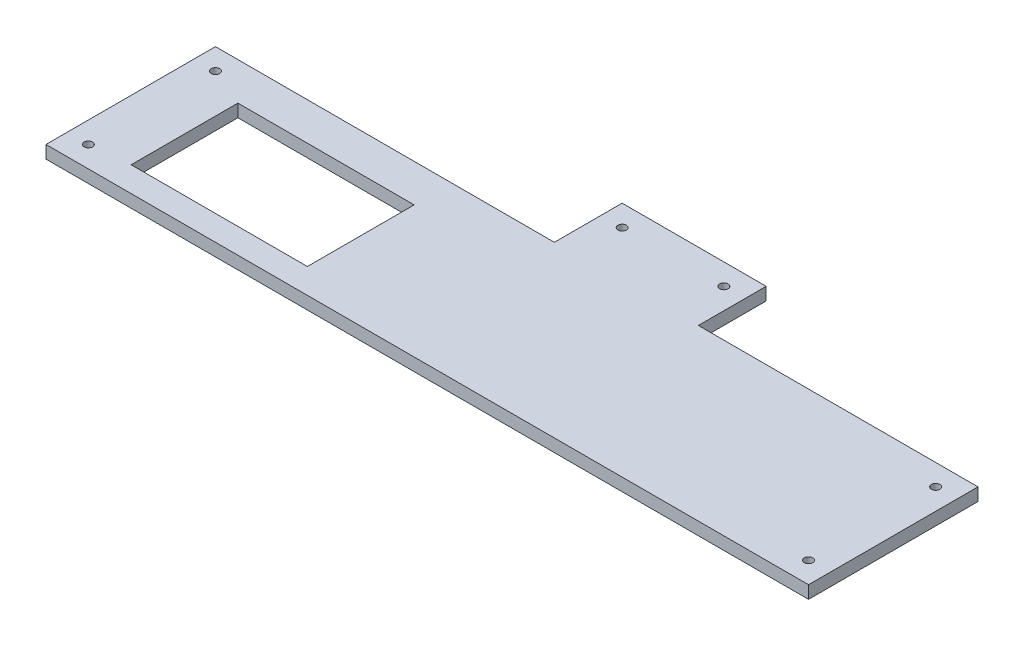
SolidWorks part; units mm, degrees
ref_plane "Front Plane" through (0, 0, 0) normal (0, 0, 1) x (1, 0, 0)
ref_plane "Top Plane" through (0, 0, 0) normal (0, 1, 0) x (1, 0, 0)
ref_plane "Right Plane" through (0, 0, 0) normal (1, 0, 0) x (0, 0, -1)
sketch "Sketch1" plane through (0, 0, 0) normal (0, 1, 0) x (1, 0, 0)
  line L0 (0, 0) -> (-450, 0) construction
  line L1 (0, 0) -> (0, 100) construction
  line L8 (450, 100) -> (-450, 100)
  line L9 (-450, 100) -> (-450, -100)
  line L10 (-450, -100) -> (450, -100)
  line L11 (450, -100) -> (450, 100)
  circle A4 centre (425, -75) radius 5
  circle A5 centre (425, 75) radius 5
  circle A6 centre (-425, -75) radius 5
  circle A7 centre (-425, 75) radius 5
  dimension "D4" = 25
  dimension "D1" = 900
  dimension "D2" = 200
  dimension "D3" = 25
extrude "Boss-Extrude1" add sketch "Sketch1" against normal blind 15
sketch "Sketch2" plane through (0, -15, 0) normal (0, -1, 0) x (1, 0, 0)
  line L1 (-379, 70.5) -> (-171, 70.5)
  line L2 (-379, 70.5) -> (-379, -55.5)
  line L3 (-379, -55.5) -> (-171, -55.5)
  line L4 (-171, 70.5) -> (-171, -55.5)
extrude "Shredder Opening" cut sketch "Sketch2" against normal through all
sketch "Sketch3" plane through (0, 0, 0) normal (0, 1, 0) x (1, 0, 0)
  line L0 (450, 100) -> (-450, 100) construction
  line L1 (120, 100) -> (-50, 100)
  line L2 (120, 100) -> (120, 180)
  line L3 (120, 180) -> (-50, 180)
  line L4 (-50, 100) -> (-50, 180)
  line L8 (35, 180) -> (35, 267.7218) construction
  line L9 (35, -331.1732) -> (35, 95.1732) construction
  line L10 (-30, -73) -> (-30, 145) construction
  line L11 (100, 155) -> (-30, 155) construction
  circle A0 centre (95, 155) radius 5 construction
  circle A1 centre (95, 155) radius 5
  circle A2 centre (-25, 155) radius 5
  dimension "D1" = 20
  dimension "D2" = 25
extrude "Legs add on" add sketch "Sketch3" against normal through all
